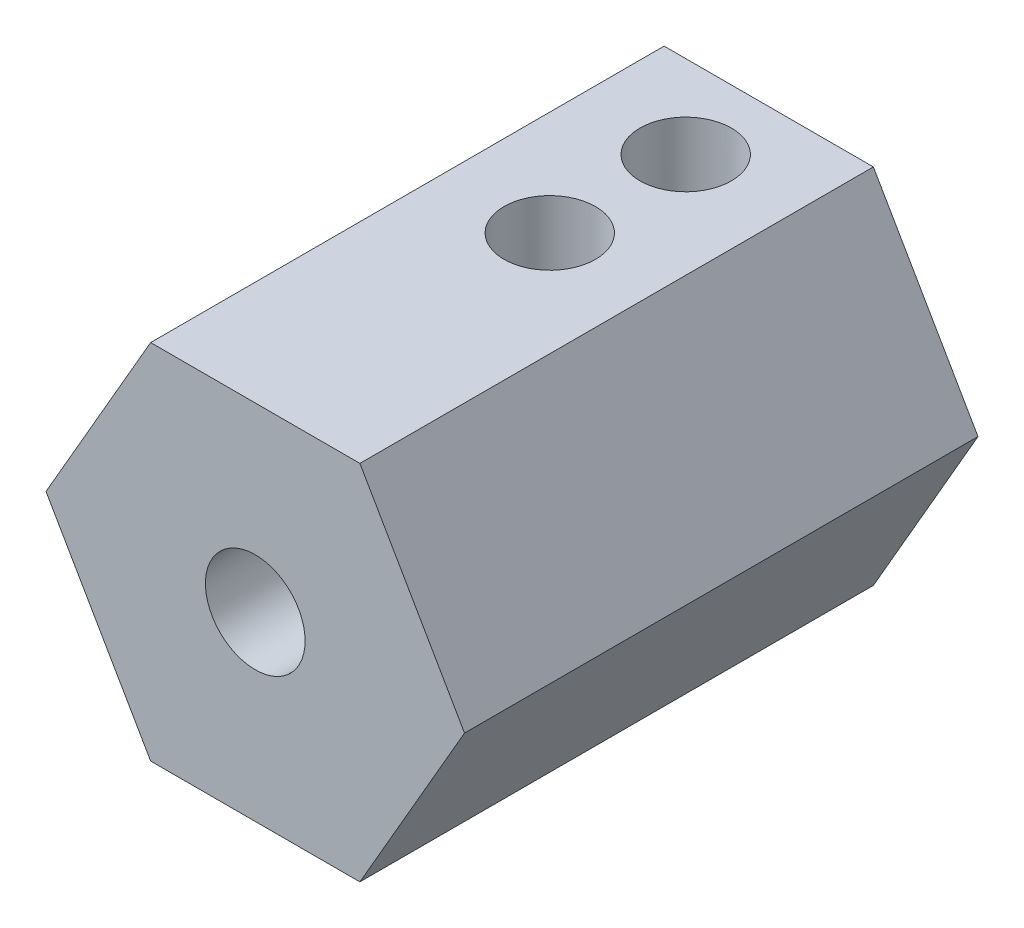
SolidWorks part; units mm, degrees
ref_plane "Front Plane" through (0, 0, 0) normal (0, 0, 1) x (1, 0, 0)
ref_plane "Top Plane" through (0, 0, 0) normal (0, 1, 0) x (1, 0, 0)
ref_plane "Right Plane" through (0, 0, 0) normal (1, 0, 0) x (0, 0, -1)
sketch "S01 - 17 mm commercial drive hex" plane through (0, 0, 0) normal (0, 0, 1) x (1, 0, 0)
  line L0 (6.9282, 0) -> (3.4641, 6)
  line L1 (3.4641, 6) -> (-3.4641, 6)
  line L2 (-3.4641, 6) -> (-6.9282, 0)
  line L3 (-6.9282, 0) -> (-3.4641, -6)
  line L4 (-3.4641, -6) -> (3.4641, -6)
  line L5 (3.4641, -6) -> (6.9282, 0)
  dimension "D1" = 3.4641
  dimension "D2" = 6.9282
  dimension "D3" = 3.4641
  dimension "D4" = 6.9282
  dimension "D5" = 6
  dimension "D6" = 6
extrude "01 - 17 mm commercial drive hex" add sketch "S01 - 17 mm commercial drive hex" along normal blind 17
sketch "S02 - Shaft seat" plane through (0, 0, 0) normal (0, 0, 1) x (1, 0, 0)
  circle A0 centre (0, 0) radius 2.025
  dimension "D1" = 4.05
extrude "02 - Shaft seat" cut sketch "S02 - Shaft seat" along normal blind 10.1 from offset 0.1 offset against normal yes
sketch "S03 - Outboard M4 thread envelope" plane through (0, 0, 0) normal (0, 0, 1) x (1, 0, 0)
  circle A0 centre (0, 0) radius 1.65
  dimension "D1" = 3.3
extrude "03 - Outboard M4 thread envelope" cut sketch "S03 - Outboard M4 thread envelope" along normal blind 7.11 from offset 9.99
sketch3d "Plane points - Radial M3 set screw 1"
  point P0 (0, 0, 2.75)
  point P1 (18, 0, 2.75)
  point P2 (0, 0, -15.25)
ref_plane "Drilling plane - Radial M3 set screw 1" through (0, 0, 0) normal (0, 1, 0) x (1, 0, 0)
sketch "S04 - Radial M3 set screw 1" plane through (0, 0, 0) normal (0, 1, 0) x (1, 0, 0)
  circle A0 centre (0, -2.75) radius 1.515
  dimension "D1" = 3.03
  dimension "D2" = 2.75
extrude "04 - Radial M3 set screw 1" cut sketch "S04 - Radial M3 set screw 1" along normal blind 7
sketch3d "Plane points - Radial M3 set screw 2"
  point P0 (0, 0, 7.25)
  point P1 (18, 0, 7.25)
  point P2 (0, 0, -10.75)
ref_plane "Drilling plane - Radial M3 set screw 2" through (0, 0, 0) normal (0, 1, 0) x (1, 0, 0)
sketch "S05 - Radial M3 set screw 2" plane through (0, 0, 0) normal (0, 1, 0) x (1, 0, 0)
  circle A0 centre (0, -7.25) radius 1.515
  dimension "D1" = 3.03
  dimension "D2" = 7.25
extrude "05 - Radial M3 set screw 2" cut sketch "S05 - Radial M3 set screw 2" along normal blind 7
